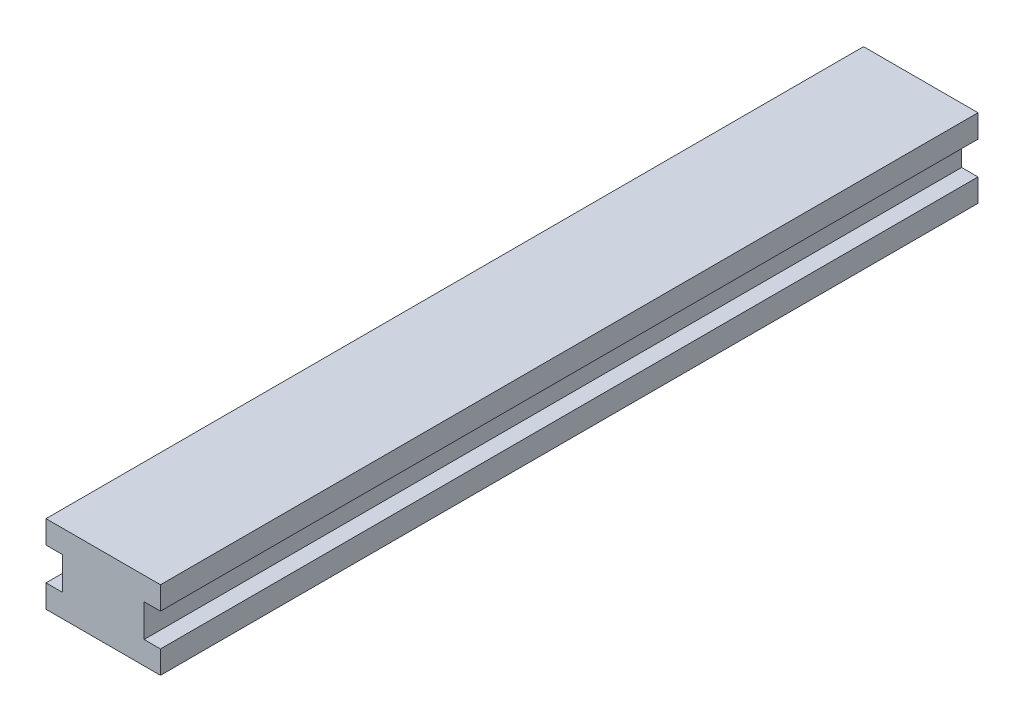
SolidWorks part; units mm, degrees
ref_plane "Front Plane" through (0, 0, 0) normal (0, 0, 1) x (1, 0, 0)
ref_plane "Top Plane" through (0, 0, 0) normal (0, 1, 0) x (1, 0, 0)
ref_plane "Right Plane" through (0, 0, 0) normal (1, 0, 0) x (0, 0, -1)
sketch "Sketch1" plane through (0, 0, 0) normal (0, 0, 1) x (1, 0, 0)
  line L1 (-3.5, -2.4) -> (3.5, -2.4)
  line L2 (-3.5, -2.4) -> (-3.5, 2.4)
  line L3 (-3.5, 2.4) -> (3.5, 2.4)
  line L4 (3.5, -2.4) -> (3.5, 2.4)
  line L5 (-3.5, -2.4) -> (3.5, 2.4) construction
  line L6 (-3.5, 2.4) -> (3.5, -2.4) construction
  line L7 (-4.5, 1) -> (-2.5, 1)
  line L8 (-4.5, 1) -> (-4.5, -1)
  line L9 (-4.5, -1) -> (-2.5, -1)
  line L10 (-2.5, 1) -> (-2.5, -1)
  line L11 (-4.5, 1) -> (-2.5, -1) construction
  line L12 (-4.5, -1) -> (-2.5, 1) construction
  line L13 (2.5, 1) -> (4.5, 1)
  line L14 (2.5, 1) -> (2.5, -1)
  line L15 (2.5, -1) -> (4.5, -1)
  line L16 (4.5, 1) -> (4.5, -1)
  line L17 (2.5, 1) -> (4.5, -1) construction
  line L18 (2.5, -1) -> (4.5, 1) construction
  point P0 (0, 0)
  point P6 (-3.5, 0)
  point P11 (3.5, 0)
  dimension "D1" = 2
  dimension "D2" = 7
  dimension "D3" = 4.8
extrude "Boss-Extrude1" add sketch "Sketch1" along normal blind 50 contours L15 L14 L13 L4 L3 L2 L7 L10 L9 L1
